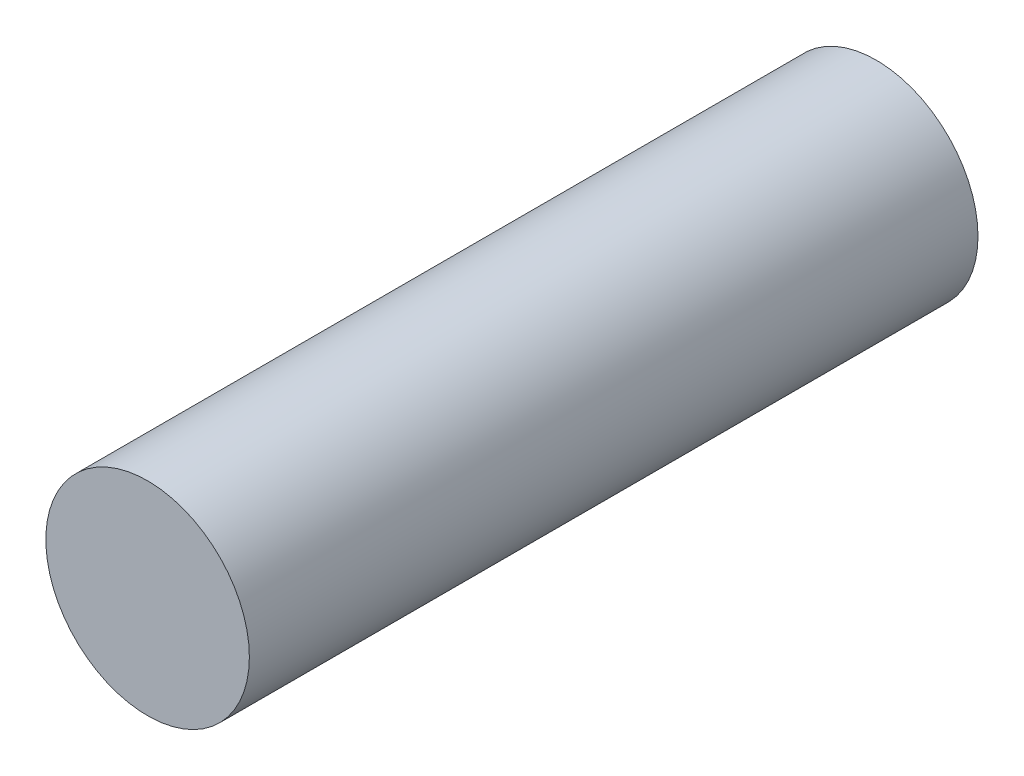
SolidWorks part; units mm, degrees
material "Li-Ion"
ref_plane "Front Plane" through (0, 0, 0) normal (0, 0, 1) x (1, 0, 0)
ref_plane "Top Plane" through (0, 0, 0) normal (0, 1, 0) x (1, 0, 0)
ref_plane "Right Plane" through (0, 0, 0) normal (1, 0, 0) x (0, 0, -1)
sketch "Sketch1" plane through (0, 0, 0) normal (0, 0, 1) x (1, 0, 0)
  circle A0 centre (0, 0) radius 9.05
  dimension "D1" = 18.1
extrude "Cell" add sketch "Sketch1" along normal blind 64.8
